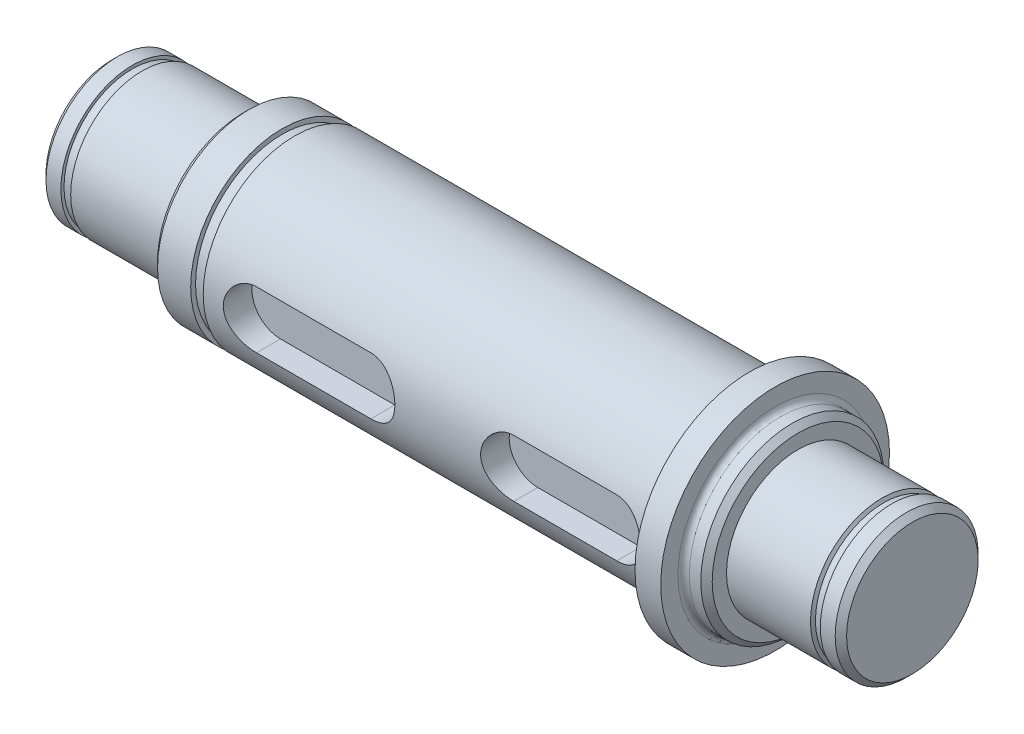
SolidWorks part; units mm, degrees
ref_plane "Piano frontale" through (0, 0, 0) normal (0, 0, 1) x (1, 0, 0)
ref_plane "Piano superiore" through (0, 0, 0) normal (0, 1, 0) x (1, 0, 0)
ref_plane "Piano destro" through (0, 0, 0) normal (1, 0, 0) x (0, 0, -1)
sketch "Schizzo1" plane through (0, 0, 0) normal (0, 0, 1) x (1, 0, 0)
  line L0 (0, 0) -> (0, 12.5)
  line L2 (23, 12.5) -> (23, 16)
  line L8 (120, 16) -> (120, 12.5)
  line L10 (140, 12.5) -> (140, 0)
  line L11 (0, 0) -> (140, 0) construction
  line L12 (0, 0) -> (140, 0)
  line L15 (29.8, 15.15) -> (29.8, 16)
  line L16 (29.8, 16) -> (23, 16)
  line L21 (116, 16) -> (120, 16)
  line L24 (29.8, 15.15) -> (31.5, 15.15)
  line L27 (31.5, 15.15) -> (31.9907, 16)
  line L34 (0, 12.5) -> (3.6, 12.5)
  line L35 (3.6, 12.5) -> (3.6, 11.95)
  line L36 (3.6, 11.95) -> (5, 11.95)
  line L37 (5, 11.95) -> (5.3175, 12.5)
  line L38 (5.3175, 12.5) -> (23, 12.5)
  line L39 (120, 12.5) -> (134.6825, 12.5)
  line L40 (134.6825, 12.5) -> (135, 11.95)
  line L41 (135, 11.95) -> (136.4, 11.95)
  line L42 (136.4, 11.95) -> (136.4, 12.5)
  line L43 (136.4, 12.5) -> (140, 12.5)
  line L44 (31.9907, 16) -> (111.5, 16)
  line L45 (111.5, 16) -> (111.5, 20)
  line L46 (111.5, 20) -> (116, 20)
  line L47 (116, 20) -> (116, 16)
  point P4 (120, 14.25)
  dimension "D3" = 20
  dimension "D4" = 18
  dimension "D6" = 23
  dimension "D7" = 80
  dimension "D8" = 1.7
  dimension "D9" = 16
  dimension "D10" = 140
  dimension "12" = 20
  dimension "D11" = 16
  dimension "D12" = 4
  dimension "D15" = 16
  dimension "D18" = 1.4
  dimension "D19" = 15.15
  dimension "D20" = 12.5
  dimension "D21" = 12.5
  dimension "D22" = 11.95
  dimension "D23" = 60
  dimension "D24" = 15
  dimension "D25" = 60
  dimension "D26" = 1.4
  dimension "D27" = 12.5
  dimension "D28" = 12.5
  dimension "D29" = 11.95
  dimension "7" = 8.5
revolve "Rivoluzione1" add sketch "Schizzo1" angle 360 about L11
ref_plane "Piano1" through (0, 0, 16) normal (0, 0, 1) x (1, 0, 0)
sketch "Schizzo2" plane through (0, 0, 16) normal (0, 0, 1) x (1, 0, 0)
  line L0 (40.5, 0) -> (60.5, 0) construction
  line L2 (40.5, 5) -> (60.5, 5)
  line L3 (40.5, -5) -> (60.5, -5)
  line L4 (85.5, 0) -> (103.5, 0) construction
  line L5 (85.5, 5) -> (103.5, 5)
  line L6 (85.5, -5) -> (103.5, -5)
  line L7 (111.5, 16) -> (111.5, -16) construction
  arc A0 (40.5, 5) -> (40.5, -5) centre (40.5, 0) ccw
  arc A1 (60.5, -5) -> (60.5, 5) centre (60.5, 0) ccw
  arc A2 (85.5, 5) -> (85.5, -5) centre (85.5, 0) ccw
  arc A3 (103.5, -5) -> (103.5, 5) centre (103.5, 0) ccw
  point P11 (65.5, 0)
  point P12 (108.5, 0)
  dimension "D1" = 10
  dimension "D2" = 20
  dimension "10" = 10
  dimension "D3" = 3
  dimension "D4" = 10
  dimension "D5" = 10
  dimension "D7" = 46
  dimension "D6" = 18
extrude "Taglio-Estrusione1" cut sketch "Schizzo2" against normal blind 5
chamfer "Smusso1" distance 1 angle 45 1 edges at (0, 0, 12.5)
chamfer "Smusso2" distance 1 angle 45 1 edges at (140, 0, 12.5)
chamfer "Smusso3" distance 1 angle 45 2 edges at (23, 0, 16) (120, 0, 16)
fillet "Raccordo3" radius 1 2 edges at (111.5, 0, 16) (116, 0, 16)
